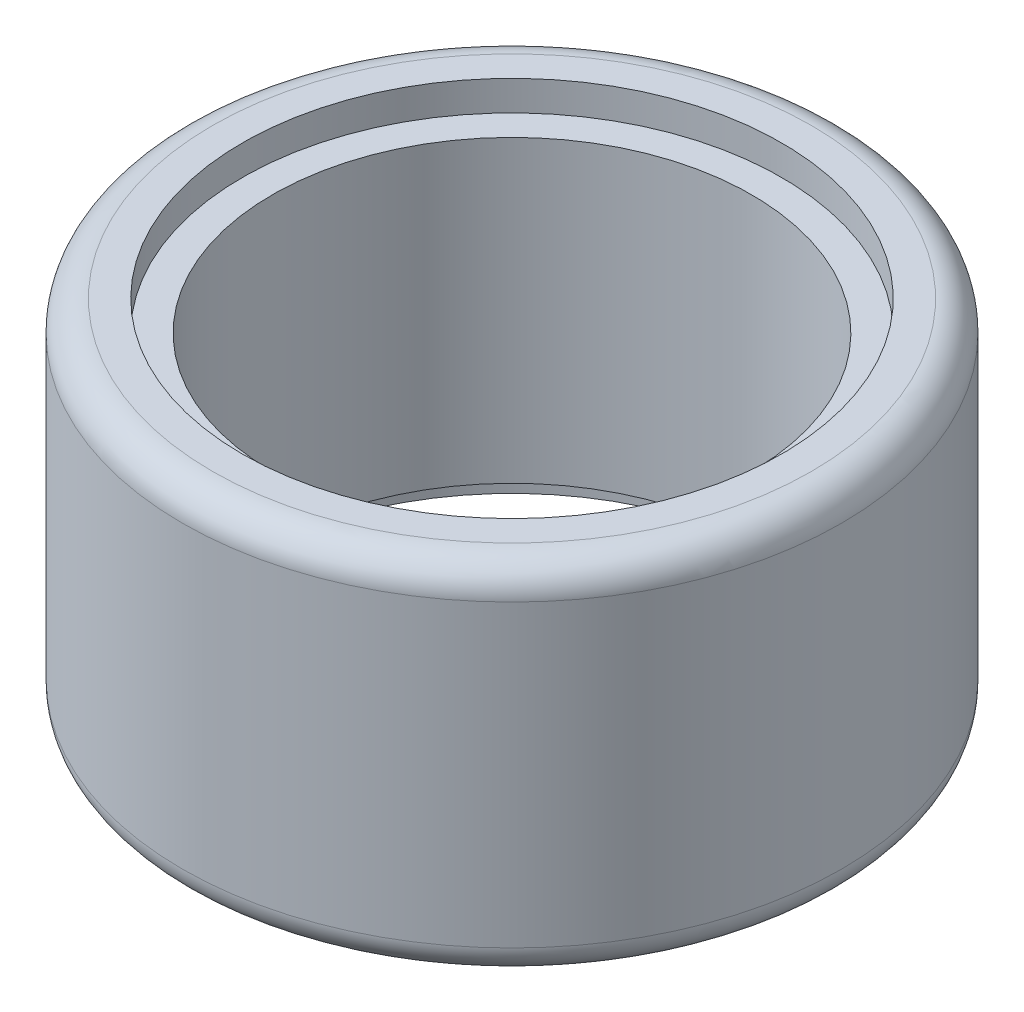
SolidWorks part; units mm, degrees
ref_plane "Front Plane" through (0, 0, 0) normal (0, 0, 1) x (1, 0, 0)
ref_plane "Top Plane" through (0, 0, 0) normal (0, 1, 0) x (1, 0, 0)
ref_plane "Right Plane" through (0, 0, 0) normal (1, 0, 0) x (0, 0, -1)
sketch "Sketch1" plane through (0, 0, 0) normal (0, 1, 0) x (1, 0, 0)
  circle A0 centre (0, 0) radius 8
  circle A1 centre (0, 0) radius 11
  dimension "D1" = 16
  dimension "D2" = 22
extrude "Boss-Extrude1" add sketch "Sketch1" along normal mid plane 12
fillet "Fillet1" radius 1 2 edges at (0, -6, 11) (0, 6, 11)
sketch "Sketch2" plane through (0, 6, 0) normal (0, 1, 0) x (1, 0, 0)
  circle A0 centre (0, 0) radius 8 construction
  circle A1 centre (0, 0) radius 8
  circle A2 centre (0, 0) radius 9
  dimension "D1" = 1
extrude "Cut-Extrude1" cut sketch "Sketch2" against normal blind 1
mirror "Mirror1" about plane through (0, 0, 0) normal (0, 1, 0) of "Cut-Extrude1"
